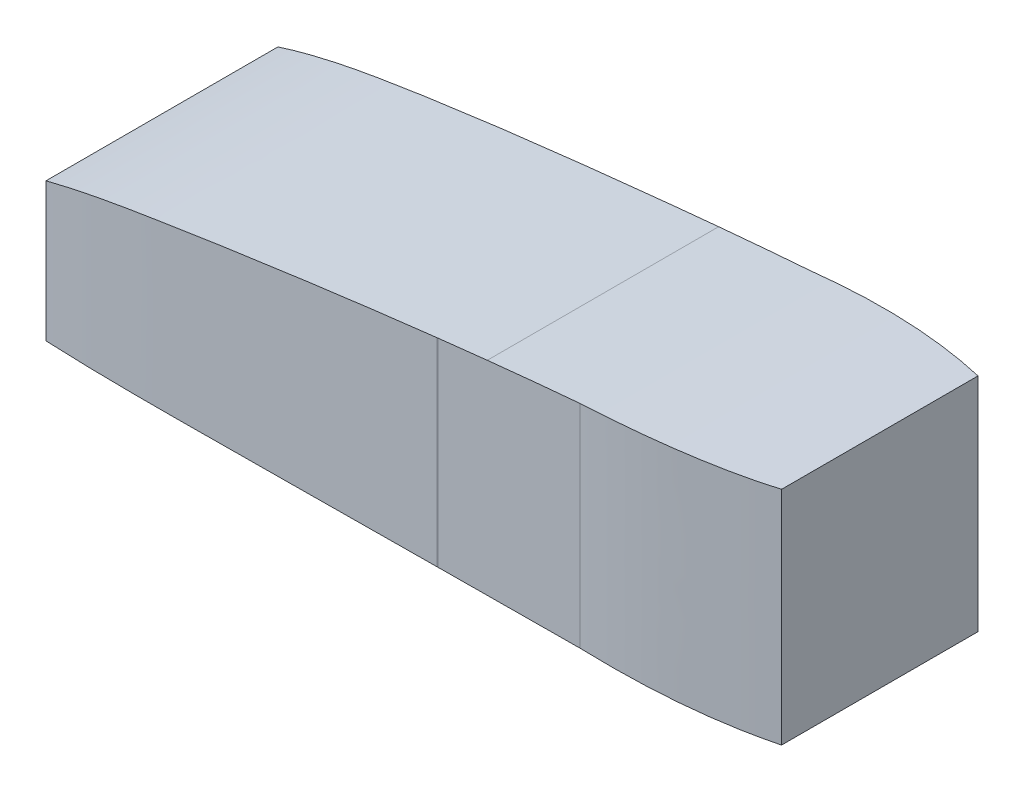
SolidWorks part; units mm, degrees
ref_plane "Front Plane" through (0, 0, 0) normal (0, 0, 1) x (1, 0, 0)
ref_plane "Top Plane" through (0, 0, 0) normal (0, 1, 0) x (1, 0, 0)
ref_plane "Right Plane" through (0, 0, 0) normal (1, 0, 0) x (0, 0, -1)
sketch "Sketch1" plane through (0, 0, 0) normal (0, 1, 0) x (1, 0, 0)
  line L0 (-824.0703, 319.8883) -> (-824.0774, 319.8882)
  line L1 (85.8918, 315.7028) -> (89.0288, 315.6785)
  line L2 (976.4063, -267.2398) -> (976.4063, 267.2398)
  line L3 (-976.4063, -315.4413) -> (-976.4063, 315.4413)
  line L4 (89.6375, -315.6738) -> (87.6402, -315.6892)
  line L5 (-976.4063, 0) -> (976.4063, 0) construction
  line L6 (0, 0) -> (0, -316.387) construction
  line L7 (0, 0) -> (0, 316.4669) construction
  spline S0 degree 3 poles (89.6375, -315.6738) (217.7655, -314.6845) (345.8942, -313.7875) (474.0237, -313.0031) knots 0.00297 0.00297 0.00297 0.00297 1 1 1 1
  spline S1 degree 3 poles (-976.4063, -315.4413) (-799.0737, -323.7264) (-621.509, -321.1628) (-266.7906, -318.7162) (-89.5762, -317.0596) (87.6402, -315.6892) knots 0 0 0 0 0.5 0.5 0.9992 0.9992 0.9992 0.9992
  spline S2 degree 3 poles (-824.0774, 319.8882) (-874.8689, 319.13) (-925.6487, 317.8127) (-976.4063, 315.4413) knots 0 0 0 0 1 1 1 1
  spline S3 degree 3 poles (85.8918, 315.7028) (-217.4344, 318.0696) (-520.8343, 324.4146) (-824.0703, 319.8883) knots 0.00285 0.00285 0.00285 0.00285 1 1 1 1
  spline S4 degree 3 poles (474.0237, 313.0031) (345.6912, 313.7888) (217.3597, 314.6873) (89.0288, 315.6785) knots 0 0 0 0 0.998609 0.998609 0.998609 0.998609
  spline S5 degree 3 poles (976.4063, 267.2398) (849.4088, 299.8791) (686.6692, 319.6411) (474.0237, 313.0031) knots 0.571508 0.571508 0.571508 0.571508 1 1 1 1
  spline S6 degree 3 poles (474.0237, -313.0031) (686.6692, -319.6411) (849.4088, -299.8791) (976.4063, -267.2398) knots 0.571508 0.571508 0.571508 0.571508 1 1 1 1
sketch "Sketch2" plane through (0, 0, 0) normal (0, 0, 1) x (1, 0, 0)
  line L0 (-976.4063, 0) -> (976.4063, 0)
  line L1 (0, 0) -> (0, 530.0004) construction
  line L2 (-976.4063, 377.2607) -> (-976.4063, 825.628)
  line L4 (-976.4063, 825.628) -> (976.4063, 825.628)
  line L5 (-976.4063, 377.2607) -> (-976.4063, 0)
  line L6 (976.4063, 602.6278) -> (976.4063, 0)
  line L7 (976.4063, 825.628) -> (976.4063, 602.6278)
  spline S8 degree 3 poles (223.3937, 553.8894) (-83.3413, 523.1796) (-513.7044, 467.8203) (-830.4433, 415.2391) (-933.334, 389.731) (-976.4063, 377.2607) knots 0.108777 0.108777 0.108777 0.108777 0.189662 0.216203 0.23816 0.23816 0.23816 0.23816
  spline S9 degree 3 poles (976.4063, 602.6278) (862.8891, 599.1114) (646.8976, 592.1824) (369.7796, 568.5414) (223.3937, 553.8894) knots 0.033635 0.033635 0.033635 0.033635 0.070138 0.108742 0.108742 0.108742 0.108742
extrude "Boss-Extrude1" add sketch "Sketch1" along normal blind 750
extrude "Cut-Extrude1" cut sketch "Sketch2" against normal through all both and the other way through all contours S9 L7 L4 L2 S8
